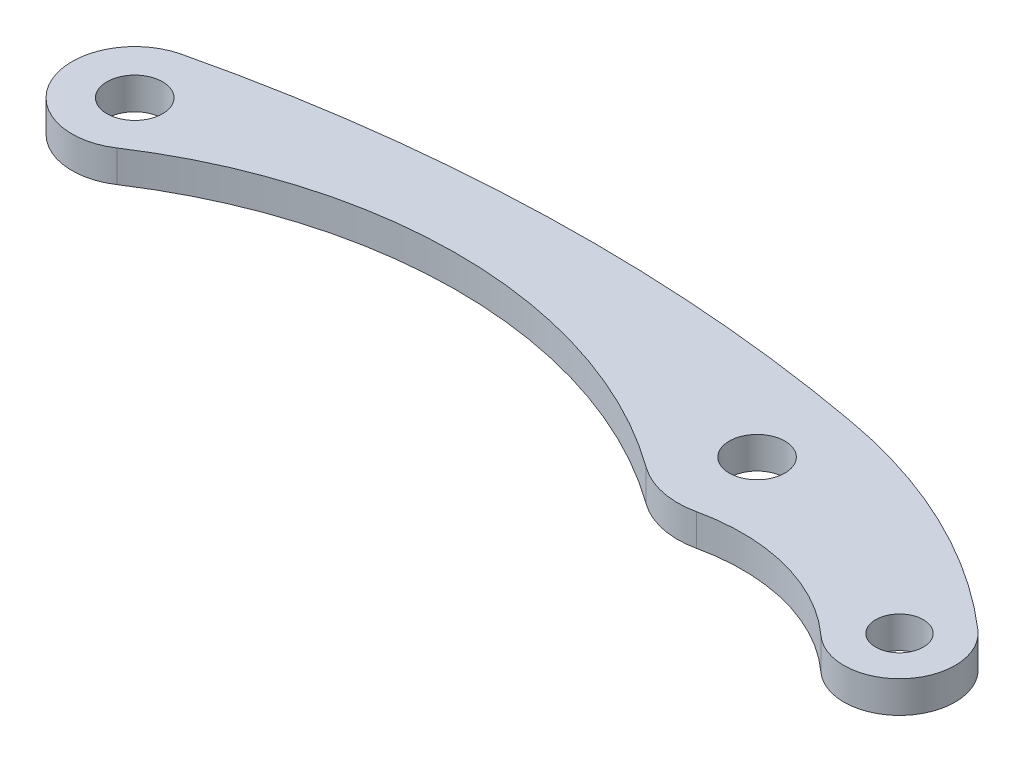
SolidWorks part; units mm, degrees
ref_plane "Front Plane" through (0, 0, 0) normal (0, 0, 1) x (1, 0, 0)
ref_plane "Top Plane" through (0, 0, 0) normal (0, 1, 0) x (1, 0, 0)
ref_plane "Right Plane" through (0, 0, 0) normal (1, 0, 0) x (0, 0, -1)
sketch "Sketch1" plane through (0, 0, 0) normal (0, 1, 0) x (1, 0, 0)
  line L0 (0, 25.5178) -> (0, -32.2544) construction
  line L1 (0, 0) -> (39.1784, 0) construction
  line L2 (39.1784, 0) -> (88.4884, 0) construction
  line L4 (39.1784, 0) -> (78.5826, -14.3419) construction
  arc A0 (-0.9109, 3.8435) -> (2.1717, -3.2995) centre (0, 0) ccw
  arc A2 (2.1717, -3.2995) -> (36.248, -4.0512) centre (18.6653, -28.3586) cw
  arc A3 (-0.9109, 3.8435) -> (40.0578, 4.9221) centre (22.1493, -93.4613) cw
  circle A4 centre (0, 0) radius 1.75
  circle A5 centre (39.1784, 0) radius 1.75
  arc A8 (36.248, -4.0512) -> (40.2575, -4.8822) centre (39.1784, 0) ccw
  circle A9 centre (53.2738, -5.1303) radius 3.5
  arc A10 (40.0578, 4.9221) -> (55.5761, -2.4941) centre (34.5264, -26.5962) cw
  arc A11 (40.2575, -4.8822) -> (50.9194, -7.7201) centre (42.8474, -16.5994) cw
  dimension "D2" = 7.9
  dimension "D3" = 10
  dimension "D4" = 100
  dimension "D5" = 30
  dimension "D6" = 3.5
  dimension "D7" = 3.5
  dimension "D8" = 200
  dimension "D10" = 12
  dimension "D9" = 7
  dimension "D11" = 32
  dimension "D1" = 39.1784
  dimension "D12" = 15
extrude "Boss-Extrude3" add sketch "Sketch1" along normal blind 2 contours A8 A11 A9 A10 A3 A0 A2 A4 A5 | A9
sketch "Sketch3" plane through (0, 2, 0) normal (0, 1, 0) x (1, 0, 0)
  circle A0 centre (53.2738, -5.1303) radius 1.5
  dimension "D1" = 3
extrude "Cut-Extrude1" cut sketch "Sketch3" against normal through all
